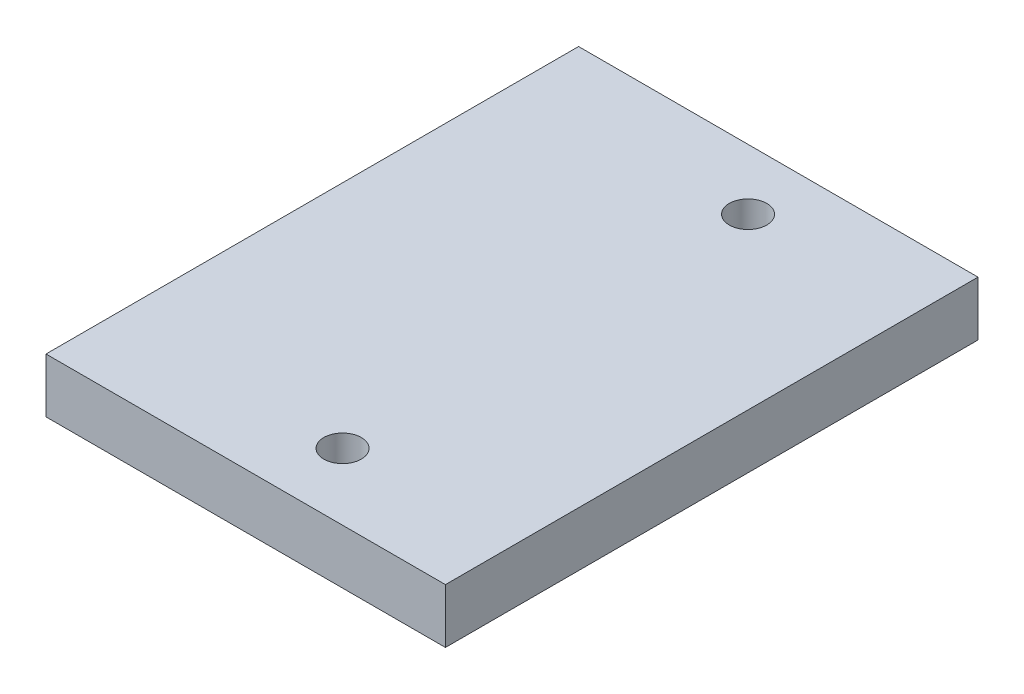
SolidWorks part; units mm, degrees
ref_plane "Alzado" through (0, 0, 0) normal (0, 0, 1) x (1, 0, 0)
ref_plane "Planta" through (0, 0, 0) normal (0, 1, 0) x (1, 0, 0)
ref_plane "Vista lateral" through (0, 0, 0) normal (1, 0, 0) x (0, 0, -1)
sketch "Croquis1" plane through (0, 0, 0) normal (0, 1, 0) x (1, 0, 0)
  line L1 (0, 0) -> (37, 0)
  line L2 (0, 0) -> (0, 44)
  line L3 (0, 44) -> (37, 44)
  line L4 (37, 0) -> (37, 44)
  dimension "D1" = 44
  dimension "D2" = 37
extrude "Saliente-Extruir1" add sketch "Croquis1" along normal blind 4.5
sketch "Croquis2" plane through (0, 4.5, 0) normal (0, 1, 0) x (1, 0, 0)
  line L0 (0, 44) -> (0, 0) construction
  line L1 (37, 44) -> (0, 44) construction
  circle A0 centre (19, 39) radius 1.55
  circle A1 centre (19, 5.5) radius 1.55
  dimension "D2" = 3.1
  dimension "D1" = 19
  dimension "D3" = 33.5
  dimension "D4" = 5
extrude "Cortar-Extruir1" cut sketch "Croquis2" against normal up to surface (4.5 mm away) up to face at (18.5, 0, -22)
sketch "Croquis3" plane through (0, 4.5, 0) normal (0, 1, 0) x (1, 0, 0)
  line L0 (37, 44) -> (0, 44) construction
  line L1 (33, 44) -> (34.5, 44)
  line L2 (33, 44) -> (33, 0)
  line L3 (33, 0) -> (34.5, 0)
  line L4 (34.5, 44) -> (34.5, 0)
  line L5 (0, 0) -> (37, 0) construction
  circle A0 centre (19, 39) radius 1.55 construction
  dimension "D1" = 1.5
  dimension "D2" = 14
extrude "Cortar-Extruir2" cut sketch "Croquis3" against normal blind 1
sketch "Croquis4" plane through (0, 0, 0) normal (0, -1, 0) x (1, 0, 0)
  line L0 (37, -44) -> (0, -44) construction
  line L1 (34.5, -44) -> (33, -44)
  line L2 (34.5, -44) -> (34.5, 0)
  line L3 (34.5, 0) -> (33, 0)
  line L4 (33, -44) -> (33, 0)
  line L5 (0, 0) -> (37, 0) construction
  circle A0 centre (19, -39) radius 1.55 construction
  dimension "D1" = 1.5
  dimension "D2" = 14
extrude "Cortar-Extruir3" cut sketch "Croquis4" against normal blind 1
sketch "Croquis8" plane through (0, 4.5, 0) normal (0, 1, 0) x (1, 0, 0)
  line L1 (33, 0) -> (37, 0)
  line L2 (33, 0) -> (33, 44)
  line L3 (33, 44) -> (37, 44)
  line L4 (37, 0) -> (37, 44)
extrude "Cortar-Extruir4" cut sketch "Croquis8" against normal up to surface (4.5 mm away) up to face at (16.5, 0, -22)
